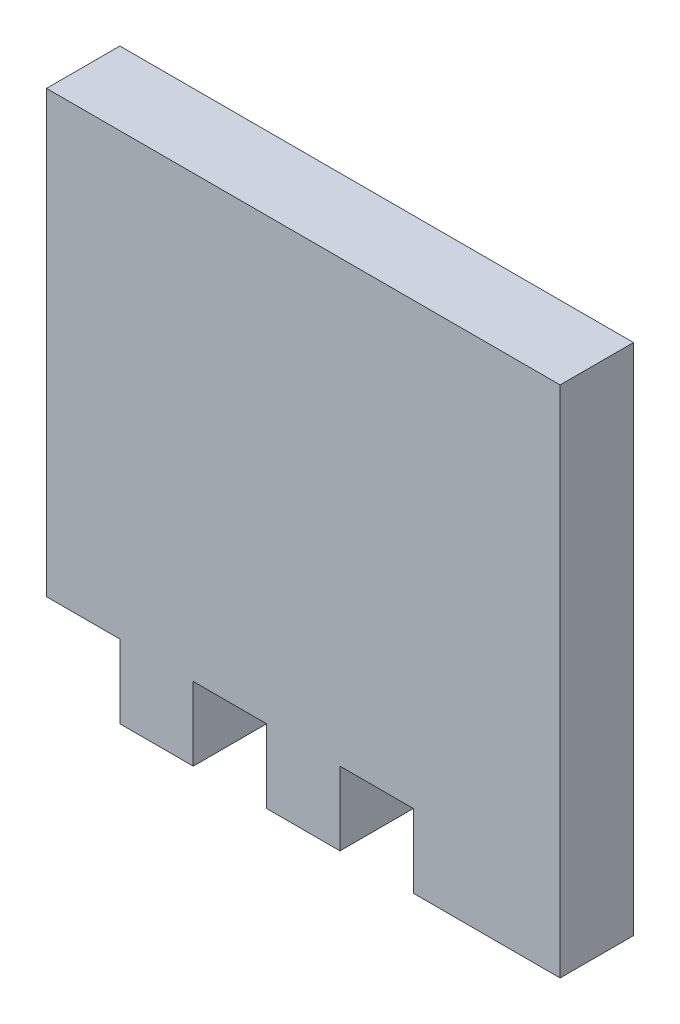
SolidWorks part; units mm, degrees
ref_plane "Plan de face" through (0, 0, 0) normal (0, 0, 1) x (1, 0, 0)
ref_plane "Plan de dessus" through (0, 0, 0) normal (0, 1, 0) x (1, 0, 0)
ref_plane "Plan de droite" through (0, 0, 0) normal (1, 0, 0) x (0, 0, -1)
sketch "Esquisse1" plane through (0, 0, 0) normal (0, 0, 1) x (1, 0, 0)
  line L0 (-68.9999, 0) -> (-63.9999, 0)
  line L1 (-63.9999, 0) -> (-63.9999, -5)
  line L2 (-63.9999, -5) -> (-58.9999, -5)
  line L3 (-58.9999, -5) -> (-58.9999, 0)
  line L4 (-58.9999, 0) -> (-53.9999, 0)
  line L5 (-53.9999, 0) -> (-53.9999, -5)
  line L7 (-33.9999, -5) -> (-33.9999, 30)
  line L8 (-68.9999, 0) -> (-68.9999, 30)
  line L9 (-68.9999, 30) -> (-33.9999, 30)
  line L10 (-53.9999, -5) -> (-48.9999, -5)
  line L11 (-48.9999, -5) -> (-48.9999, 0)
  line L12 (-48.9999, 0) -> (-43.9999, 0)
  line L13 (-43.9999, 0) -> (-43.9999, -5)
  line L14 (-43.9999, -5) -> (-33.9999, -5)
  dimension "D1" = 30
  dimension "D2" = 5
  dimension "D3" = 5
  dimension "D4" = 10
extrude "Boss.-Extru.1" add sketch "Esquisse1" along normal blind 5
